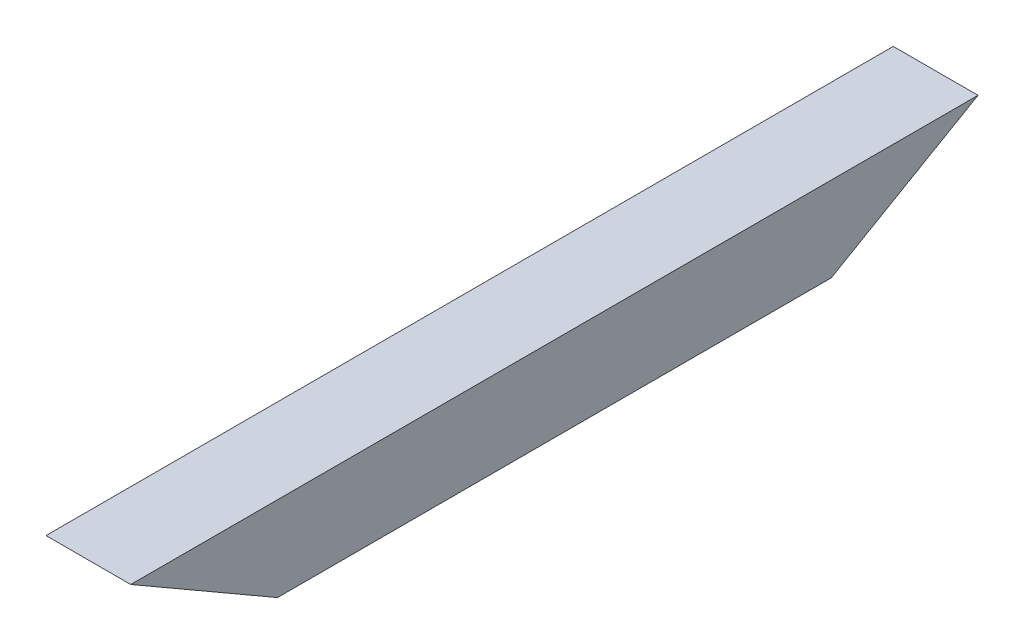
SolidWorks part; units mm, degrees
material "AISI 1020"
ref_plane "Front Plane" through (0, 0, 0) normal (0, 0, 1) x (1, 0, 0)
ref_plane "Top Plane" through (0, 0, 0) normal (0, 1, 0) x (1, 0, 0)
ref_plane "Right Plane" through (0, 0, 0) normal (1, 0, 0) x (0, 0, -1)
sketch "Sketch1" plane through (0, 0, 0) normal (0, 0, 1) x (1, 0, 0)
  line L0 (22.225, 22.225) -> (22.225, 25.4) construction
  line L1 (-25.4, -25.4) -> (25.4, -25.4)
  line L2 (-25.4, -25.4) -> (-25.4, 25.4)
  line L3 (-25.4, 25.4) -> (25.4, 25.4)
  line L4 (25.4, -25.4) -> (25.4, 25.4)
  line L5 (-25.4, -25.4) -> (25.4, 25.4) construction
  line L6 (-25.4, 25.4) -> (25.4, -25.4) construction
  line L7 (-22.225, -22.225) -> (22.225, -22.225)
  line L8 (-22.225, -22.225) -> (-22.225, 22.225)
  line L9 (-22.225, 22.225) -> (22.225, 22.225)
  line L10 (22.225, -22.225) -> (22.225, 22.225)
  line L11 (-22.225, -22.225) -> (22.225, 22.225) construction
  line L12 (-22.225, 22.225) -> (22.225, -22.225) construction
  line L13 (22.225, -22.225) -> (25.4, -22.225) construction
  point P0 (0, 0)
  point P6 (0, 0)
  dimension "D2" = 50.8
  dimension "D3" = 3.175
extrude "Boss-Extrude1" add sketch "Sketch1" along normal blind 508
sketch "Sketch2" plane through (-25.4, 0, 0) normal (-1, 0, 0) x (0, 0, 1)
  line L0 (0, 25.4) -> (87.9882, -25.4)
  line L1 (508, -25.4) -> (0, -25.4) construction
  line L2 (87.9882, -25.4) -> (0, -25.4)
  line L3 (0, -25.4) -> (0, 25.4)
  line L4 (508, 25.4) -> (420.0118, -25.4)
  line L5 (420.0118, -25.4) -> (508, -25.4)
  line L6 (508, -25.4) -> (508, 25.4)
  dimension "D1" = 30
  dimension "D2" = 60
extrude "Cut-Extrude1" cut sketch "Sketch2" against normal through all
